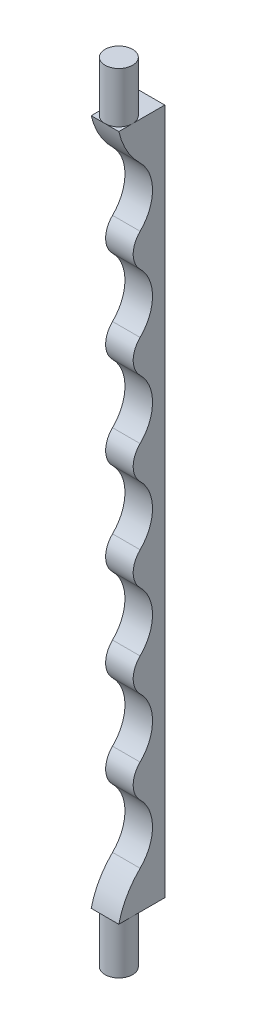
SolidWorks part; units mm, degrees
ref_plane "Front Plane" through (0, 0, 0) normal (1, 0, 0) x (0, 1, 0)
ref_plane "Top Plane" through (0, 0, 0) normal (0, 0, 1) x (0, 1, 0)
ref_plane "Right Plane" through (0, 0, 0) normal (0, 1, 0) x (-1, 0, 0)
sketch "Sketch1" plane through (0, 0, 0) normal (1, 0, 0) x (0, 1, 0)
  line L2 (-112, -2.5) -> (-112, -17.5)
  line L3 (-112, -17.5) -> (112, -17.5)
  line L6 (112, -2.5) -> (112, -17.5)
  line L11 (-1106.2497, -2.5) -> (48893.7503, -2.5) construction
  arc A0 (-9.6429, -9.448) -> (9.6429, -9.448) centre (0, 0) ccw
  arc A1 (20.3571, -9.448) -> (39.6429, -9.448) centre (30, 0) ccw
  arc A2 (50.3571, -9.448) -> (69.6429, -9.448) centre (60, 0) ccw
  arc A3 (80.3571, -9.448) -> (99.6429, -9.448) centre (90, 0) ccw
  arc A4 (-39.6429, -9.448) -> (-20.3571, -9.448) centre (-30, 0) ccw
  arc A5 (-69.6429, -9.448) -> (-50.3571, -9.448) centre (-60, 0) ccw
  arc A6 (-99.6429, -9.448) -> (-80.3571, -9.448) centre (-90, 0) ccw
  arc A7 (-69.6429, -9.448) -> (-80.3571, -9.448) centre (-75, -14.6969) ccw
  arc A8 (-39.6429, -9.448) -> (-50.3571, -9.448) centre (-45, -14.6969) ccw
  arc A9 (-9.6429, -9.448) -> (-20.3571, -9.448) centre (-15, -14.6969) ccw
  arc A10 (20.3571, -9.448) -> (9.6429, -9.448) centre (15, -14.6969) ccw
  arc A11 (50.3571, -9.448) -> (39.6429, -9.448) centre (45, -14.6969) ccw
  arc A12 (80.3571, -9.448) -> (69.6429, -9.448) centre (75, -14.6969) ccw
  arc A17 (-99.6429, -9.448) -> (-112, -2.5) centre (-117.7503, -27.1896) ccw
  arc A18 (99.6429, -9.448) -> (112, -2.5) centre (117.7503, -27.1896) cw
  dimension "D1" = 27
  dimension "D6" = 15
  dimension "D7" = 15
  dimension "D8" = 15
  dimension "D9" = 15
  dimension "D10" = 15
  dimension "D11" = 15
  dimension "D12" = 2.5
  dimension "D13" = 2.5
  dimension "D14" = 15
  dimension "D3" = 30
  dimension "D5" = 30
  dimension "D17" = 112
  dimension "D18" = 112
  dimension "D2" = 4
  dimension "D4" = 4
extrude "Boss-Extrude1" add sketch "Sketch1" along normal blind 9
sketch "Sketch2" plane through (0, -112, 0) normal (0, -1, 0) x (1, 0, 0)
  line L0 (9, -17.5) -> (0, -17.5) construction
  line L1 (4.5, -1017.5) -> (4.5, 48982.5) construction
  line L4 (9, -2.5) -> (0, -2.5) construction
  circle A1 centre (4.5, -7) radius 4.5
  point P8 (4.5, -17.5)
  dimension "D1" = 9
extrude "Boss-Extrude2" add sketch "Sketch2" along normal blind 16.5
mirror "Mirror1" about plane through (0, 0, 0) normal (0, 1, 0) of "Boss-Extrude2"
